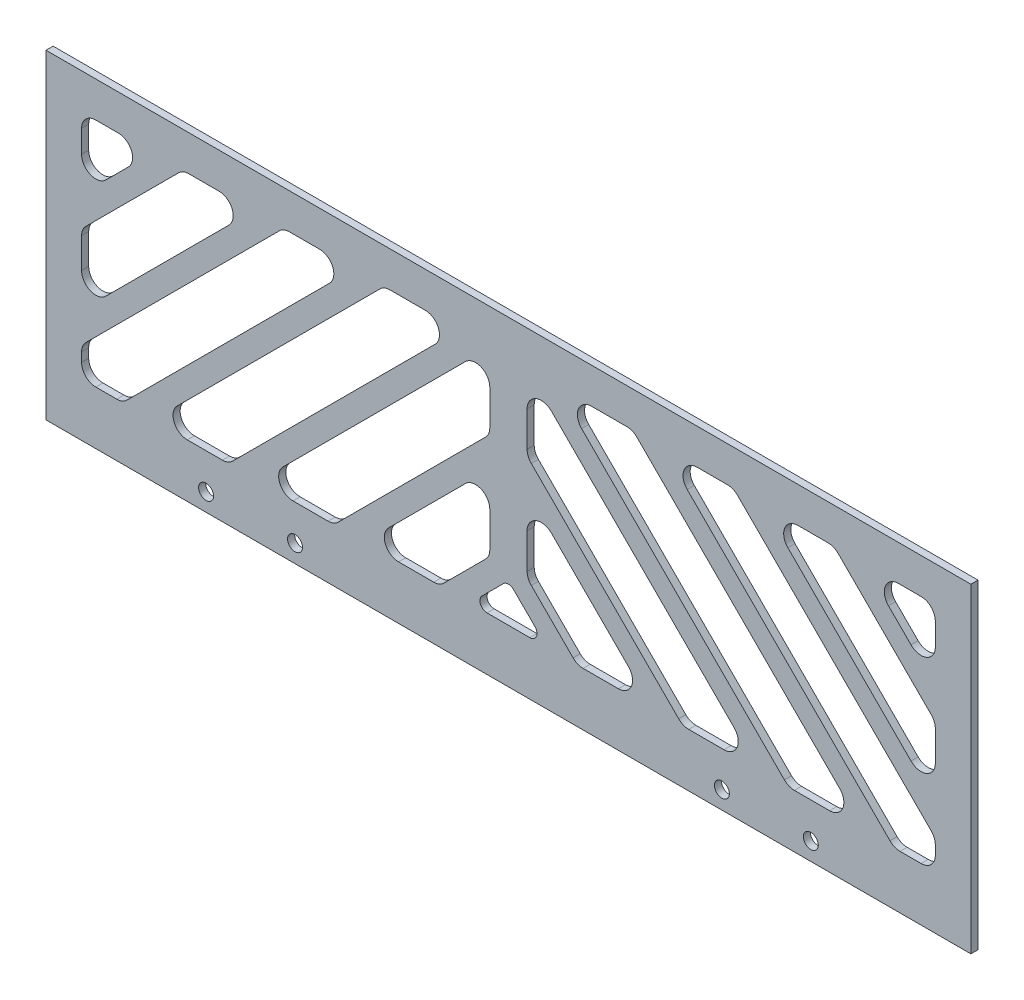
SolidWorks part; units mm, degrees
material "环氧树脂FR-4"
ref_plane "前视基准面" through (0, 0, 0) normal (0, 0, 1) x (1, 0, 0)
ref_plane "上视基准面" through (0, 0, 0) normal (0, 1, 0) x (1, 0, 0)
ref_plane "右视基准面" through (0, 0, 0) normal (1, 0, 0) x (0, 0, -1)
sketch "草图1" plane through (0, 0, 0) normal (0, 0, 1) x (1, 0, 0)
  line L1 (-130, 90) -> (130, 90)
  line L2 (-130, 90) -> (-130, 0)
  line L3 (-130, 0) -> (130, 0)
  line L4 (130, 90) -> (130, 0)
  dimension "D1" = 0
  dimension "D2" = 260
  dimension "D3" = 90
  dimension "D4" = 130
extrude "凸台-拉伸1" add sketch "草图1" along normal blind 2
sketch "草图2" plane through (0, 0, 2) normal (0, 0, 1) x (1, 0, 0)
  line L0 (-130, 0) -> (130, 0) construction
  point P0 (-60, 5)
  point P3 (-85, 5)
  dimension "D1" = 5
  dimension "D3" = 60
  dimension "D4" = 25
  dimension "D2" = 2
hole_wizard "Ø4.2 (4.2) 直径孔1" positions "3D草图1" profile "草图3" hole size "Ø4.2" standard "GB" end condition through all
sketch3d "3D草图1"
  point P0 (-60, 5, 2)
  point P3 (-85, 5, 2)
sketch "草图3" plane through (-60, 5, 2) normal (1, 0, 0) x (0, -1, 0)
  line L0 (0, 0) -> (0, 2)
  line L1 (0, 2) -> (2.1, 2)
  line L2 (2.1, 2) -> (2.1, 0)
  line L5 (2.1, 0) -> (0, 0)
  line L11 (0, -6.35) -> (0, 107.95) construction
  dimension "通孔孔直径" = 4.2
  dimension "通孔孔深度" = 2
mirror "镜向1" about plane through (0, 0, 0) normal (1, 0, 0) of "Ø4.2 (4.2) 直径孔1"
sketch "草图5" plane through (0, 0, 2) normal (0, 0, 1) x (1, 0, 0)
  line L0 (-130, 0) -> (130, 0) construction
  line L1 (-120, 80) -> (-100, 80)
  line L2 (-120, 80) -> (-120, 60)
  line L3 (-120, 15) -> (-108.4315, 15)
  line L5 (-130, 90) -> (-130, 0) construction
  line L6 (130, 90) -> (-130, 90) construction
  line L7 (-5.2477, 50.3015) -> (-40.5492, 15)
  line L8 (-100, 80) -> (-120, 60)
  line L9 (-91.5147, 80) -> (-120, 51.5147)
  line L10 (-71.7157, 80) -> (-120, 31.7157)
  line L11 (-63.2304, 80) -> (-120, 23.2304)
  line L12 (-120, 51.5147) -> (-120, 31.7157)
  line L13 (-67.491, 104.0237) -> (-147.2785, 24.2363) construction
  line L14 (-91.5147, 80) -> (-71.7157, 80)
  line L15 (-63.2304, 80) -> (-43.4315, 80)
  line L16 (-57.5915, 94.1242) -> (-137.379, 14.3368) construction
  line L17 (-120, 23.2304) -> (-120, 15)
  line L18 (-43.4315, 80) -> (-108.4315, 15)
  line L19 (-53.3488, 89.8816) -> (-133.1363, 10.0941) construction
  line L20 (-34.9462, 80) -> (-99.9462, 15)
  line L21 (-13.733, 80) -> (-78.733, 15)
  line L22 (-5.2477, 80) -> (-70.2477, 15)
  line L23 (-34.9462, 80) -> (-13.733, 80)
  line L24 (13.2583, 98.506) -> (-116.6602, -31.4125) construction
  line L25 (9.0157, 102.7487) -> (-120.9029, -27.1699) construction
  line L26 (-1.5909, 113.3553) -> (-131.5095, -16.5633) construction
  line L27 (-5.8336, 117.5979) -> (-135.7521, -12.3206) construction
  line L28 (-99.9462, 15) -> (-78.733, 15)
  line L29 (-70.2477, 15) -> (-49.0345, 15)
  line L31 (-5.2477, 80) -> (-5.2477, 58.7868)
  line L32 (-5.2477, 58.7868) -> (-49.0345, 15)
  line L33 (-40.5492, 15) -> (-19.336, 15)
  line L34 (-5.2477, 29.0883) -> (-5.2477, 50.3015)
  line L35 (-5.2477, 29.0883) -> (-19.336, 15)
  dimension "D1" = 15
  dimension "D2" = 10
  dimension "D3" = 10
  dimension "D4" = 6
  dimension "D5" = 20
  dimension "D6" = 20
  dimension "D7" = 6
  dimension "D10" = 14
  dimension "D14" = 15
  dimension "D15" = 15
  dimension "D16" = 0
  dimension "D17" = 15
  dimension "D8" = 14
  dimension "D9" = 6
  dimension "D11" = 6
  dimension "D12" = 15
  dimension "D13" = 6
extrude "切除-拉伸1" cut sketch "草图5" against normal through all
fillet "圆角1" radius 4 24 edges at (-49.0345, 15, 1) (-70.2477, 15, 1) (-5.2477, 58.7868, 1) (-5.2477, 80, 1) (-13.733, 80, 1) (-34.9462, 80, 1) (-78.733, 15, 1) (-99.9462, 15, 1) (-108.4315, 15, 1) (-120, 15, 1) (-120, 23.2304, 1) (-43.4315, 80, 1) (-63.2304, 80, 1) (-71.7157, 80, 1) (-120, 31.7157, 1) (-91.5147, 80, 1) (-120, 51.5147, 1) (-120, 60, 1) (-100, 80, 1) (-120, 80, 1) (-5.2477, 50.3015, 1) (-5.2477, 29.0883, 1) (-19.336, 15, 1) (-40.5492, 15, 1)
mirror "镜向2" about plane through (0, 0, 0) normal (1, 0, 0) of "圆角1", "切除-拉伸1"
sketch "草图6" plane through (0, 0, 2) normal (0, 0, 1) x (1, 0, 0)
  line L0 (-1.4142, 24.4365) -> (-7.4365, 18.4142)
  line L1 (0, -1.1) -> (0, 1.1) construction
  line L2 (-6.0223, 15) -> (6.0223, 15)
  line L3 (7.4365, 18.4142) -> (1.4142, 24.4365)
  line L5 (-18.1644, 16.1716) -> (-6.4193, 27.9167) construction
  line L6 (18.1644, 16.1716) -> (6.4193, 27.9167) construction
  line L7 (-130, 0) -> (130, 0) construction
  arc A0 (6.0223, 15) -> (7.4365, 18.4142) centre (6.0223, 17) ccw
  arc A1 (-7.4365, 18.4142) -> (-6.0223, 15) centre (-6.0223, 17) ccw
  arc A2 (-1.4142, 24.4365) -> (1.4142, 24.4365) centre (0, 23.0223) cw
  point P17 (0, 25.8507)
  dimension "D3" = 2
  dimension "D1" = 15
  dimension "D2" = 6
extrude "切除-拉伸2" cut sketch "草图6" against normal through all
